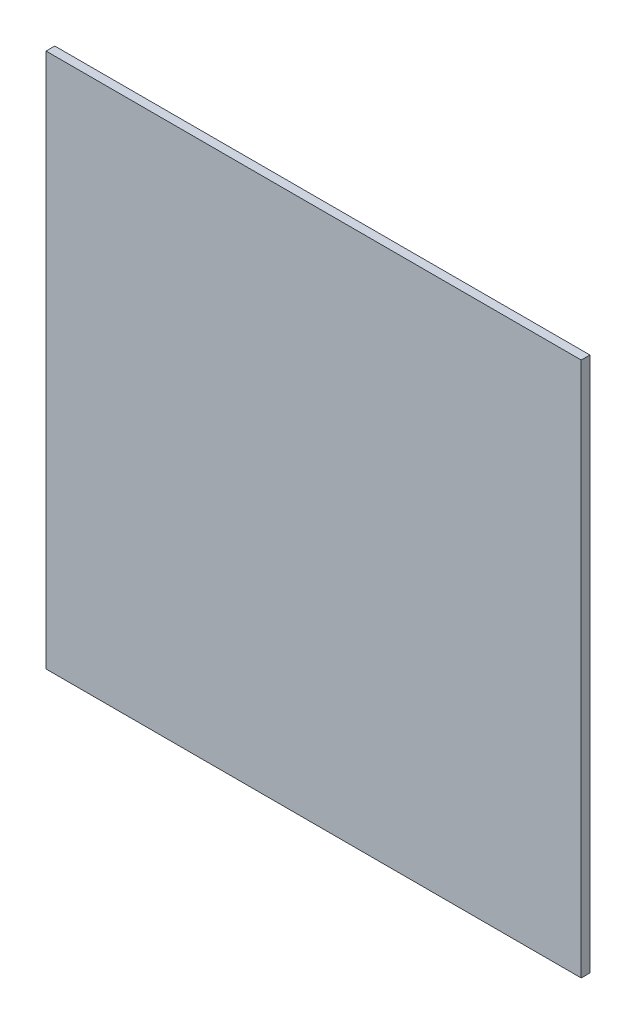
SolidWorks part; units mm, degrees
material "ABS PC"
ref_plane "Front Plane" through (0, 0, 0) normal (0, 0, 1) x (1, 0, 0)
ref_plane "Top Plane" through (0, 0, 0) normal (0, 1, 0) x (1, 0, 0)
ref_plane "Right Plane" through (0, 0, 0) normal (1, 0, 0) x (0, 0, -1)
sketch "Sketch1" plane through (418.3886, -1281.7256, 334.2736) normal (0, 0, 1) x (1, 0, 0)
  line L1 (-60.8493, -230.2696) -> (123.3007, -230.2696)
  line L2 (-60.8493, -230.2696) -> (-60.8493, -46.1196)
  line L3 (-60.8493, -46.1196) -> (123.3007, -46.1196)
  line L4 (123.3007, -230.2696) -> (123.3007, -46.1196)
  line L5 (-60.8493, -230.2696) -> (123.3007, -46.1196) construction
  line L6 (-60.8493, -46.1196) -> (123.3007, -230.2696) construction
  dimension "D1" = 184.15
  dimension "D2" = 184.15
extrude "Boss-Extrude1" add sketch "Sketch1" along normal blind 3 contours L4 L3 L2 L1
equation "\"D1@Sketch1\"=\"frame_width@frame section-1.Part\"+2*\"groove_depth@frame section-1.Part\"-2*\"frame_thickness@frame section-1.Part\""
equation "\"D1@Boss-Extrude1\"=\"rear_panel_thickness@frame section-1.Part\""
